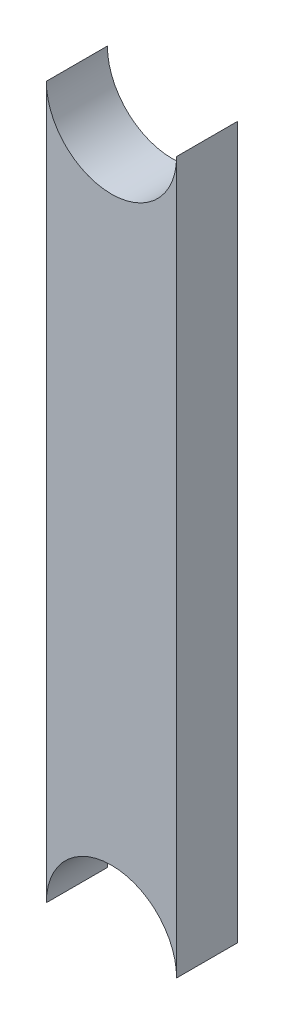
SolidWorks part; units mm, degrees
material "Titanium"
ref_plane "Front Plane" through (0, 0, 0) normal (0, 0, 1) x (1, 0, 0)
ref_plane "Top Plane" through (0, 0, 0) normal (0, 1, 0) x (1, 0, 0)
ref_plane "Right Plane" through (0, 0, 0) normal (1, 0, 0) x (0, 0, -1)
sketch "Sketch1" plane through (0, 0, 0) normal (0, 0, 1) x (1, 0, 0)
  line L1 (-3.2, 0) -> (-3.2, 34.9448)
  line L2 (3.2, 34.9448) -> (3.2, 0)
  line L3 (0, -1.65) -> (0, 1.65) construction
  arc A2 (3.2, 0) -> (-3.2, 0) centre (0, 0) ccw
  arc A3 (-3.2, 34.9448) -> (3.2, 34.9448) centre (0, 34.9448) ccw
  dimension "D1" = 6.4
  dimension "D2" = 34.9448
extrude "Boss-Extrude3" add sketch "Sketch1" along normal blind 3
equation "\"bScale\"= 8"
equation "\"lScale\"= 8"
equation "\"D1@Sketch1\"=.8*\"bScale\""
equation "\"D2@Sketch1\"=4.3681*\"lScale\""
